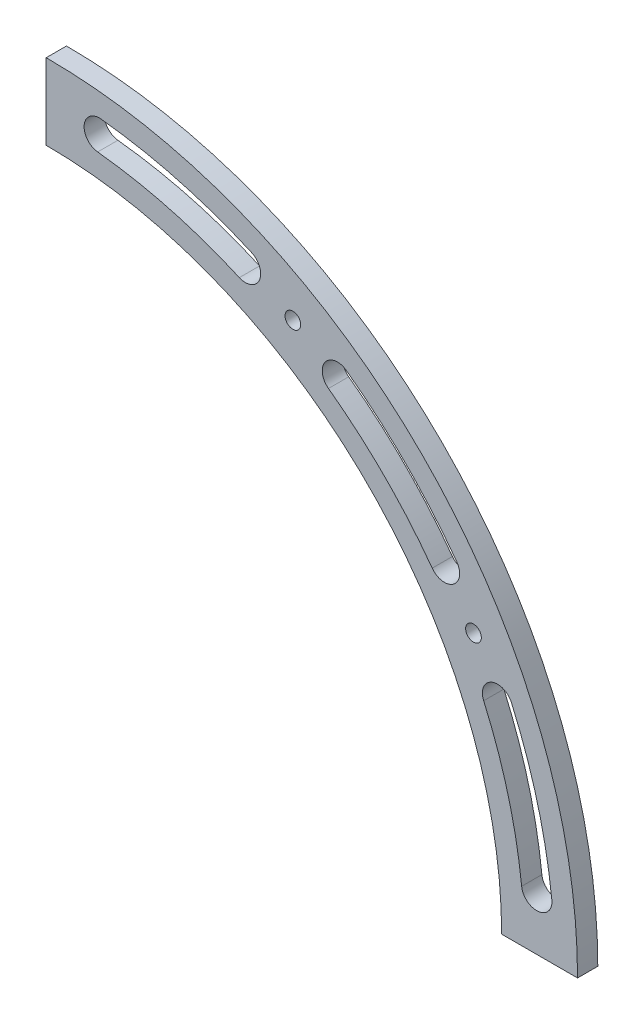
SolidWorks part; units mm, degrees
material "Thornel Mat VMA"
ref_plane "前视基准面" through (0, 0, 0) normal (0, 0, 1) x (1, 0, 0)
ref_plane "上视基准面" through (0, 0, 0) normal (0, 1, 0) x (1, 0, 0)
ref_plane "右视基准面" through (0, 0, 0) normal (1, 0, 0) x (0, 0, -1)
other "Configuration Table"
sketch "草图1" plane through (0, 0, 0) normal (0, 0, 1) x (1, 0, 0)
  line L0 (0, 105) -> (0, 0) construction
  line L1 (0, 0) -> (105, 0) construction
  line L2 (90, 0) -> (105, 0)
  line L3 (0, 105) -> (0, 90)
  arc A0 (0, 105) -> (105, 0) centre (0, 0) cw
  arc A1 (0, 90) -> (90, 0) centre (0, 0) cw
  dimension "D1" = 105
  dimension "D2" = 90
extrude "凸台-拉伸1" add sketch "草图1" along normal blind 15
sketch "草图2" plane through (0, 0, 0) normal (0, -1, 0) x (1, 0, 0)
  line L1 (90, 15) -> (105, 15)
  line L2 (90, 15) -> (90, 0)
  line L3 (90, 0) -> (105, 0)
  line L4 (105, 15) -> (105, 0)
extrude "凸台-拉伸2" add sketch "草图2" along normal blind 5
sketch "草图3" plane through (105, 0, 0) normal (1, 0, 0) x (0, 0, -1)
  line L0 (0, -5) -> (50, -5) construction
  line L1 (50, -5) -> (50, -55) construction
  line L2 (50, -55) -> (50, -70)
  line L3 (-15, -5) -> (0, -5)
  arc A0 (0, -5) -> (50, -55) centre (50, -5) ccw
  arc A1 (-15, -5) -> (50, -70) centre (50, -5) ccw
  dimension "D1" = 50
extrude "凸台-拉伸3" add sketch "草图3" against normal blind 15
sketch "草图4" plane through (0, 0, 15) normal (0, 0, 1) x (1, 0, 0)
  line L0 (25.2349, 94.1778) -> (0, 0) construction
  line L1 (0, 0) -> (68.9429, 68.9429) construction
  line L2 (0, 0) -> (94.1778, 25.2349) construction
  line L3 (0, 0) -> (90, 0) construction
  line L4 (48.75, 84.4375) -> (0, 0) construction
  line L5 (84.4375, 48.75) -> (0, 0) construction
  arc A0 (10.4903, 96.934) -> (39.3822, 89.1925) centre (0, 0) cw construction
  arc A1 (40.5939, 91.9368) -> (10.813, 99.9166) centre (0, 0) ccw
  arc A2 (38.1704, 86.4481) -> (10.1675, 93.9514) centre (0, 0) ccw
  arc A3 (38.1704, 86.4481) -> (40.5939, 91.9368) centre (39.3822, 89.1925) ccw
  arc A4 (10.813, 99.9166) -> (10.1675, 93.9514) centre (10.4903, 96.934) ccw
  arc A5 (57.5518, 78.7022) -> (78.7022, 57.5518) centre (0, 0) cw construction
  arc A6 (81.1238, 59.3227) -> (59.3227, 81.1238) centre (0, 0) ccw
  arc A7 (76.2806, 55.781) -> (55.781, 76.2806) centre (0, 0) ccw
  arc A8 (76.2806, 55.781) -> (81.1238, 59.3227) centre (78.7022, 57.5518) ccw
  arc A9 (59.3227, 81.1238) -> (55.781, 76.2806) centre (57.5518, 78.7022) ccw
  arc A10 (89.1925, 39.3822) -> (96.934, 10.4903) centre (0, 0) cw construction
  arc A11 (99.9166, 10.813) -> (91.9368, 40.5939) centre (0, 0) ccw
  arc A12 (93.9514, 10.1675) -> (86.4481, 38.1704) centre (0, 0) ccw
  arc A13 (93.9514, 10.1675) -> (99.9166, 10.813) centre (96.934, 10.4903) ccw
  arc A14 (91.9368, 40.5939) -> (86.4481, 38.1704) centre (89.1925, 39.3822) ccw
  circle A17 centre (84.4375, 48.75) radius 1.55
  circle A18 centre (48.75, 84.4375) radius 1.55
  point P4 (25.2349, 94.1778)
  point P9 (68.9429, 68.9429)
  point P18 (94.1778, 25.2349)
  dimension "D1" = 3
  dimension "D2" = 3
  dimension "D3" = 3
  dimension "D7" = 97.5
  dimension "D8" = 97.5
  dimension "D9" = 97.5
  dimension "D12" = 3.1
  dimension "D13" = 3.1
  dimension "D14" = 15
  dimension "D4" = 15
  dimension "D5" = 45
  dimension "D6" = 75
  dimension "D10" = 97.5
  dimension "D11" = 97.5
  dimension "D15" = 15
  dimension "D16" = 15
  dimension "D17" = 15
  dimension "D18" = 15
sketch "草图5" plane through (105, 0, 0) normal (1, 0, 0) x (0, 0, -1)
  line L0 (-2.1127, -29.3006) -> (50, -5) construction
  line L1 (50, -5) -> (25.6994, -57.1127) construction
  line L2 (50, -55) -> (50, -5) construction
  line L3 (50, -5) -> (0, -5) construction
  line L4 (-7.2812, -10.0115) -> (50, -5) construction
  line L5 (50, -5) -> (9.3414, -45.6586) construction
  line L6 (50, -5) -> (44.9694, -62.5) construction
  arc A0 (-5.5348, -19.9043) -> (2.8856, -37.9618) centre (50, -5) ccw construction
  arc A1 (-8.4322, -20.6819) -> (0.4274, -39.6816) centre (50, -5) ccw
  arc A2 (-2.6373, -19.1267) -> (5.3437, -36.2421) centre (50, -5) ccw
  arc A3 (-2.6373, -19.1267) -> (-8.4322, -20.6819) centre (-5.5348, -19.9043) ccw
  arc A4 (0.4274, -39.6816) -> (5.3437, -36.2421) centre (2.8856, -37.9618) ccw
  arc A5 (17.0382, -52.1144) -> (35.0957, -60.5348) centre (50, -5) ccw construction
  arc A6 (15.3184, -54.5726) -> (34.3181, -63.4322) centre (50, -5) ccw
  arc A7 (18.7579, -49.6563) -> (35.8733, -57.6373) centre (50, -5) ccw
  arc A8 (18.7579, -49.6563) -> (15.3184, -54.5726) centre (17.0382, -52.1144) ccw
  arc A9 (34.3181, -63.4322) -> (35.8733, -57.6373) centre (35.0957, -60.5348) ccw
  circle A13 centre (44.9694, -62.5) radius 1.55
  circle A14 centre (9.3414, -45.6586) radius 1.55
  circle A15 centre (-7.2812, -10.0115) radius 1.55
  point P4 (-2.1127, -29.3006)
  point P9 (25.6994, -57.1127)
  dimension "D1" = 57.5
  dimension "D2" = 57.5
  dimension "D8" = 3.1
  dimension "D9" = 3.1
  dimension "D10" = 3.1
  dimension "D12" = 25
  dimension "D13" = 3
  dimension "D16" = 3
  dimension "D3" = 57.5
  dimension "D4" = 57.5
  dimension "D5" = 57.5
  dimension "D6" = 10
  dimension "D7" = 10
  dimension "D11" = 45
  dimension "D14" = 5
  dimension "D15" = 5
  dimension "D17" = 25
extrude "切除-拉伸1" cut sketch "草图4" against normal through all
extrude "切除-拉伸2" cut sketch "草图5" against normal through all
sketch "草图6" plane through (105, 0, 0) normal (1, 0, 0) x (0, 0, -1)
  line L0 (50, -55) -> (50, -70)
  line L1 (0, -5) -> (-15, -5)
  arc A0 (0, -5) -> (50, -55) centre (50, -5) ccw
  arc A1 (-15, -5) -> (50, -70) centre (50, -5) ccw
extrude "切除-拉伸3" cut sketch "草图6" against normal blind 4
sketch "草图7" plane through (0, 0, 15) normal (0, 0, 1) x (1, 0, 0)
  line L0 (0, 105) -> (0, 90)
  line L1 (90, 0) -> (105, 0)
  line L2 (90, -5) -> (90, 0) construction
  arc A0 (0, 90) -> (90, 0) centre (0, 0) cw
  arc A1 (0, 105) -> (105, 0) centre (0, 0) cw
extrude "切除-拉伸4" cut sketch "草图7" against normal through all flip side to cut
sketch "草图8" plane through (0, 0, 15) normal (0, 0, 1) x (1, 0, 0)
  line L0 (0, 105) -> (0, 90)
  line L1 (90, 0) -> (105, 0)
  arc A0 (0, 90) -> (90, 0) centre (0, 0) cw
  arc A1 (0, 105) -> (105, 0) centre (0, 0) cw
extrude "切除-拉伸5" cut sketch "草图8" against normal blind 11
